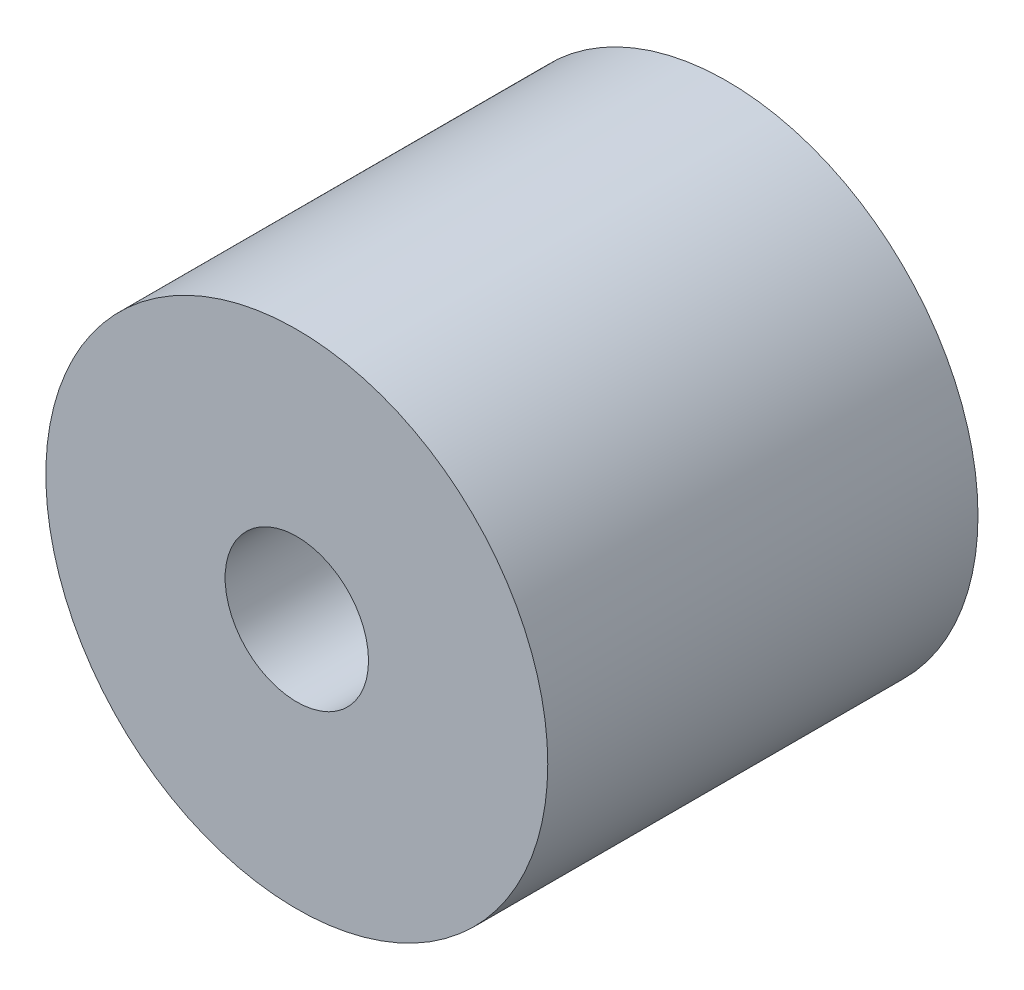
SolidWorks part; units mm, degrees
ref_plane "Front Plane" through (0, 0, 0) normal (0, 0, 1) x (1, 0, 0)
ref_plane "Top Plane" through (0, 0, 0) normal (0, 1, 0) x (1, 0, 0)
ref_plane "Right Plane" through (0, 0, 0) normal (1, 0, 0) x (0, 0, -1)
sketch "Sketch1" plane through (0, 0, 0) normal (0, 0, 1) x (1, 0, 0)
  circle A0 centre (0, 0) radius 17.5
  circle A1 centre (0, 0) radius 5
  dimension "D1" = 35
  dimension "D2" = 10
extrude "Boss-Extrude1" add sketch "Sketch1" along normal blind 30
sketch "Sketch2" plane through (0, 0, 0) normal (0, 1, 0) x (1, 0, 0)
  line L0 (0, 0) -> (0, -30) construction
  line L1 (-17.5, -30) -> (17.5, -30) construction
